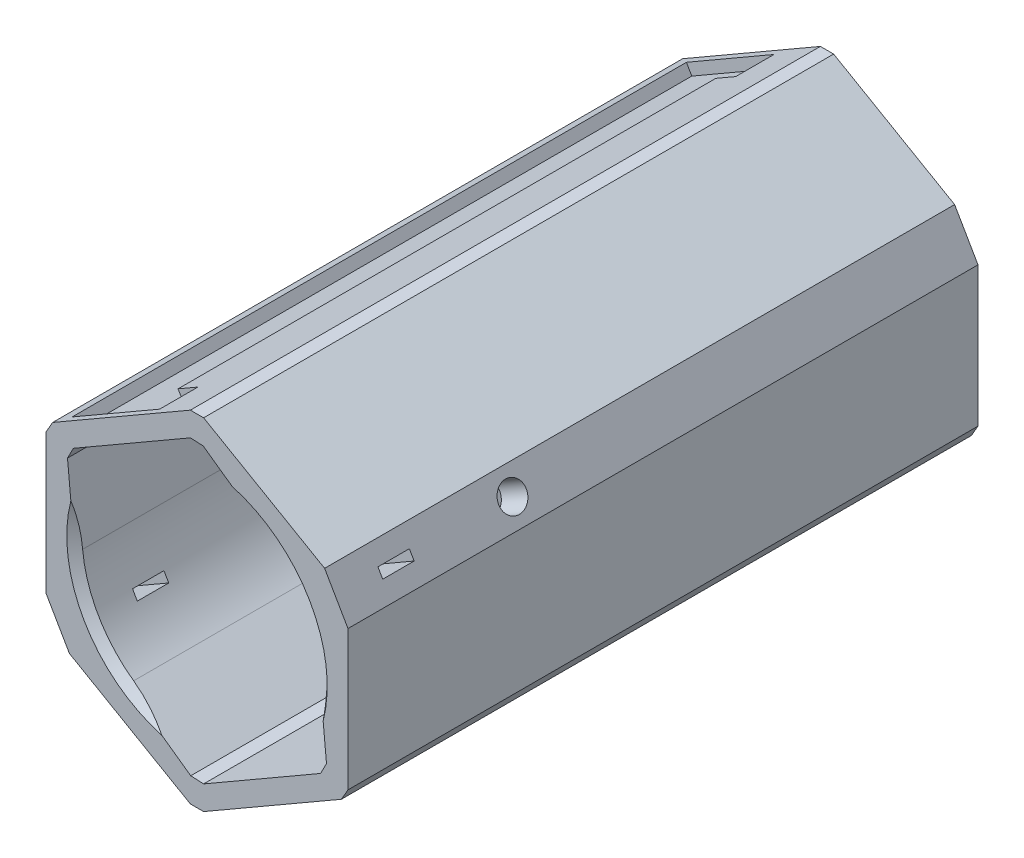
SolidWorks part; units mm, degrees
ref_plane "Front Plane" through (0, 0, 0) normal (0, 0, 1) x (1, 0, 0)
ref_plane "Top Plane" through (0, 0, 0) normal (0, 1, 0) x (1, 0, 0)
ref_plane "Right Plane" through (0, 0, 0) normal (1, 0, 0) x (0, 0, -1)
sketch "Sketch1" plane through (0, 0, 0) normal (0, 1, 0) x (1, 0, 0)
  line L0 (0, -39.84) -> (0, 48.538) construction
  line L1 (-48.4604, 0) -> (48.3051, 0) construction
  line L2 (0, 0) -> (16.125, 0)
  line L3 (16.125, 0) -> (16.125, -71)
  line L4 (16.125, -71) -> (19.65, -71)
  line L5 (19.65, -71) -> (19.65, 68)
  line L6 (19.65, 68) -> (24.95, 68)
  line L7 (24.95, 68) -> (24.95, 73)
  line L8 (24.95, 73) -> (28.1, 73)
  line L9 (28.1, 73) -> (28.1, 68)
  line L10 (28.1, 68) -> (42, 68)
  line L11 (42, 68) -> (42, 76)
  line L12 (42, 76) -> (16.65, 76)
  line L13 (16.65, 76) -> (16.65, 18.0044)
  line L14 (16.65, 18.0044) -> (12.194, 18.0044)
  line L15 (12.194, 18.0044) -> (12.194, 24.8827)
  line L16 (12.194, 24.8827) -> (0, 24.8827)
  line L17 (0, 0) -> (0, 24.8827)
  dimension "D1" = 42
  dimension "D2" = 8
  dimension "D3" = 16.125
  dimension "D4" = 19.65
  dimension "D5" = 71
  dimension "D6" = 68
  dimension "D7" = 5.3
  dimension "D8" = 3
  dimension "D9" = 3.15
  dimension "D10" = 68
  dimension "D11" = 5
revolve "Revolve1" add sketch "Sketch1" angle 360 about L0
sketch "Sketch2" plane through (0, 0, 71) normal (0, 0, 1) x (1, 0, 0)
  line L0 (0, 50.7794) -> (0, -52.6576) construction
  line L2 (0, 22.762) -> (-19.7125, 11.381)
  line L3 (-19.7125, 11.381) -> (-19.7125, -11.381)
  line L4 (-19.7125, -11.381) -> (0, -22.762)
  line L5 (0, -22.762) -> (19.7125, -11.381)
  line L6 (19.7125, -11.381) -> (19.7125, 11.381)
  line L7 (19.7125, 11.381) -> (0, 22.762)
  circle A0 centre (0, 0) radius 16
  circle A1 centre (0, 0) radius 19.7125 construction
  dimension "D1" = 32
  dimension "D2" = 39.425
extrude "Boss-Extrude1" add sketch "Sketch2" against normal blind 82.25
sketch "Sketch3" plane through (0, 0, 0) normal (0, 1, 0) x (1, 0, 0)
  line L0 (19.7125, -71) -> (0, -71) construction
  line L1 (-69.8468, 135.683) -> (82.1728, 135.683)
  line L2 (-69.8468, 135.683) -> (-69.8468, 11.25)
  line L3 (-69.8468, 11.25) -> (82.1728, 11.25)
  line L4 (82.1728, 135.683) -> (82.1728, 11.25)
  dimension "D1" = 82.25
extrude "Cut-Extrude1" cut sketch "Sketch3" against normal through all both and the other way through all
sketch "Sketch4" plane through (-9.8563, 17.0715, 0) normal (-0.5, 0.866, 0) x (0.866, 0.5, 0)
  line L0 (0, 22.8519) -> (0, -81.41) construction
  line L1 (11.381, -71) -> (-11.381, -71) construction
  line L2 (-8.6, 10.2) -> (4.6, 10.2)
  line L3 (-8.6, 10.2) -> (-8.6, -70)
  line L4 (-8.6, -70) -> (4.6, -70)
  line L5 (1.6, 5.2) -> (1.6, -65)
  line L6 (-3.5, 22.8519) -> (-3.5, -78.1641) construction
  line L8 (4.6, 10.2) -> (4.6, 5.2)
  line L9 (4.6, 5.2) -> (1.6, 5.2)
  line L10 (-54.3589, -29.9) -> (49.651, -29.9) construction
  line L11 (1.6, -65) -> (4.6, -65)
  line L12 (4.6, -65) -> (4.6, -70)
  dimension "D1" = 3
  dimension "D2" = 1
  dimension "D3" = 5.1
  dimension "D4" = 5.1
  dimension "D5" = 3.5
  dimension "D6" = 5
  dimension "D7" = 3
  dimension "D8" = 40.1
  dimension "D9" = 40.1
  dimension "D10" = 5
extrude "Cut-Extrude2" cut sketch "Sketch4" against normal blind 1.4
chamfer "Chamfer2" distance 1 6 edges at (0, -22.762, 29.875) (19.7125, -11.381, 29.875) (19.7125, 11.381, 29.875) (0, 22.762, 29.875) (-19.7125, -11.381, 29.875) (-19.7125, 11.381, 29.875)
chamfer "Chamfer3" distance 1 1 edges at (16, 0, 71)
sketch "Sketch5" plane through (0, 0, 71) normal (0, 0, 1) x (1, 0, 0)
  line L0 (0, 29.2623) -> (0, -28.2706) construction
  line L1 (-17, 9.815) -> (-15.9289, -1.507)
  line L8 (0, 19.6299) -> (-17, 9.815)
  line L11 (0, -19.6299) -> (17, -9.815)
  line L14 (-17, 9.815) -> (-17, -9.815) [skipped]
  line L15 (17, 9.815) -> (0, 19.6299) [skipped]
  line L16 (17, -9.815) -> (17, 9.815) [skipped]
  line L17 (-17, -9.815) -> (0, -19.6299) [skipped]
  line L18 (0, 19.6299) -> (9.2695, 13.0413)
  line L19 (0, -19.6299) -> (-9.2695, -13.0413)
  line L20 (17, -9.815) -> (15.9289, 1.507)
  circle A0 centre (0, 0) radius 17 construction
  arc A3 (-9.2695, -13.0413) -> (15.9289, 1.507) centre (0, 0) ccw
  arc A4 (9.2695, 13.0413) -> (-15.9289, -1.507) centre (0, 0) ccw
  dimension "D1" = 34
  dimension "D2" = 32
  dimension "D3" = 19.6299
  dimension "D4" = 19.6299
extrude "Cut-Extrude3" cut sketch "Sketch5" against normal up to surface (71 mm away) up to face at (16, 0, 0)
chamfer "Chamfer4" distance 1 4 edges at (0, -19.6299, 35.5) (17, -9.815, 35.5) (-17, 9.815, 35.5) (0, 19.6299, 35.5)
sketch "Sketch6" plane through (0, 0, -11.25) normal (0, 0, -1) x (-1, 0, 0)
  line L0 (0, 27.8377) -> (0, -30.1469) construction
  line L1 (-27.1417, 0) -> (27.0229, 0) construction
  line L8 (0, 0) -> (-7.2169, 12.5) construction
  line L9 (-7.2169, 12.5) -> (-14.4338, 0)
  line L10 (-14.4338, 0) -> (-7.2169, -12.5)
  line L11 (-7.2169, -12.5) -> (7.2169, -12.5)
  line L12 (7.2169, -12.5) -> (14.4338, 0)
  line L13 (14.4338, 0) -> (7.2169, 12.5)
  line L14 (7.2169, 12.5) -> (-7.2169, 12.5)
  circle A0 centre (0, 0) radius 12.5 construction
  dimension "D1" = 25
  dimension "D2" = 30
extrude "Cut-Extrude4" cut sketch "Sketch6" against normal blind 1.2
sketch "Sketch8" plane through (0, 0, -10.05) normal (0, 0, -1) x (-1, 0, 0)
  circle A0 centre (0, 0) radius 2.75
  dimension "D1" = 5.5
extrude "Cut-Extrude5" cut sketch "Sketch8" against normal through all
sketch "Sketch10" plane through (0, 0, 0) normal (0, 0, 1) x (1, 0, 0)
  line L0 (0, 11.9673) -> (0, -9.2947) construction
  line L1 (2.5, 10) -> (-2.5, 10)
  line L2 (-2.5, 10) -> (-2.5, 7.0711)
  line L3 (2.5, 10) -> (2.5, 7.0711)
  arc A0 (-2.5, 7.0711) -> (2.5, 7.0711) centre (0, 0) ccw
  point P9 (0, 10)
  dimension "D1" = 15
  dimension "D2" = 2.5
  dimension "D3" = 10
extrude "Cut-Extrude7" cut sketch "Sketch10" against normal blind 5
chamfer "Chamfer5" distance 0.5 4 edges at (2.5, 8.5355, 0) (0, 10, 0) (-2.5, 8.5355, 0) (0, -7.5, 0)
sketch "Sketch11" plane through (0, 0, 71) normal (0, 0, 1) x (1, 0, 0)
  line L0 (0, 0) -> (19.7125, 11.381) construction
  line L1 (-23.0929, 0) -> (26.2098, 0) construction
  line L2 (0, 0) -> (9.8563, -17.0715) construction
  line L9 (19.7125, 11.381) -> (16.6606, 13.1431)
  line L15 (0, 0) -> (0, 28.1304) construction
  line L16 (16.6606, 13.1431) -> (19.7125, 7.8569)
  line L18 (19.7125, 7.8569) -> (19.7125, 11.381)
  line L23 (-16.6606, -13.1431) -> (-19.7125, -11.381)
  line L24 (-19.7125, -7.8569) -> (-16.6606, -13.1431)
  line L25 (-19.7125, -11.381) -> (-19.7125, -7.8569)
  dimension "D1" = 30
  dimension "D3" = 21
extrude "Cut-Extrude8" cut sketch "Sketch11" against normal through all
sketch "Sketch12" plane through (-18.1865, -10.5, 0) normal (-0.866, -0.5, 0) x (0, 0, 1)
  line L0 (-22.307, 0) -> (76.3649, 0) construction
  line L1 (34, 27.3384) -> (34, -25.0984) construction
  line L2 (71, 18.8465) -> (71, 3.0519) construction
  line L3 (46, 31.7166) -> (46, -26.3202) construction
  circle A0 centre (48, 0) radius 1.8
  dimension "D3" = 3.6
  dimension "D1" = 37
  dimension "D2" = 12
  dimension "D4" = 2
extrude "Cut-Extrude9" cut sketch "Sketch12" against normal blind 4
sketch "Sketch13" plane through (18.1865, 10.5, 0) normal (0.866, 0.5, 0) x (0, 0, -1)
  circle A0 centre (-48, 0) radius 1.8 construction
  circle A1 centre (-48, 0) radius 1.8
extrude "Cut-Extrude10" cut sketch "Sketch13" against normal blind 4
sketch "Sketch14" plane through (18.1865, 10.5, 0) normal (0.866, 0.5, 0) x (0, 0, -1)
  line L0 (20.7684, 0) -> (-85.6765, 0) construction
  line L1 (-48, 5.9192) -> (-48, -6.656) construction
  line L3 (-65.25, 0.625) -> (-61.15, 0.625)
  line L4 (-65.25, 0.625) -> (-65.25, -0.625)
  line L5 (-65.25, -0.625) -> (-61.15, -0.625)
  line L6 (-61.15, 0.625) -> (-61.15, -0.625)
  dimension "D1" = 4.1
  dimension "D2" = 1.25
  dimension "D3" = 0.625
  dimension "D4" = 13.15
extrude "Cut-Extrude11" cut sketch "Sketch14" against normal through all
